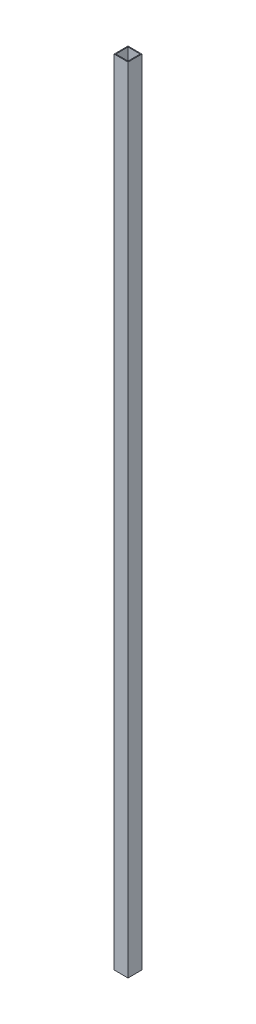
SolidWorks part; units mm, degrees
material "6061 Alloy"
ref_plane "Front Plane" through (0, 0, 0) normal (0, 0, 1) x (1, 0, 0)
ref_plane "Top Plane" through (0, 0, 0) normal (0, 1, 0) x (1, 0, 0)
ref_plane "Right Plane" through (0, 0, 0) normal (1, 0, 0) x (0, 0, -1)
sketch "Sketch1" plane through (0, 0, 0) normal (0, 1, 0) x (1, 0, 0)
  line L1 (-12.7, -12.7) -> (12.7, -12.7)
  line L2 (-12.7, -12.7) -> (-12.7, 12.7)
  line L3 (-12.7, 12.7) -> (12.7, 12.7)
  line L4 (12.7, -12.7) -> (12.7, 12.7)
  line L7 (-11.1125, -11.1125) -> (11.1125, -11.1125)
  line L8 (-11.1125, -11.1125) -> (-11.1125, 11.1125)
  line L9 (-11.1125, 11.1125) -> (11.1125, 11.1125)
  line L10 (11.1125, -11.1125) -> (11.1125, 11.1125)
  point P6 (0, 0)
  dimension "D1" = 25.4
  dimension "D2" = 25.4
  dimension "D3" = 1.5875
  dimension "D4" = 1.5875
  dimension "D5" = 1.5875
extrude "Boss-Extrude1" add sketch "Sketch1" along normal blind 1447.8
